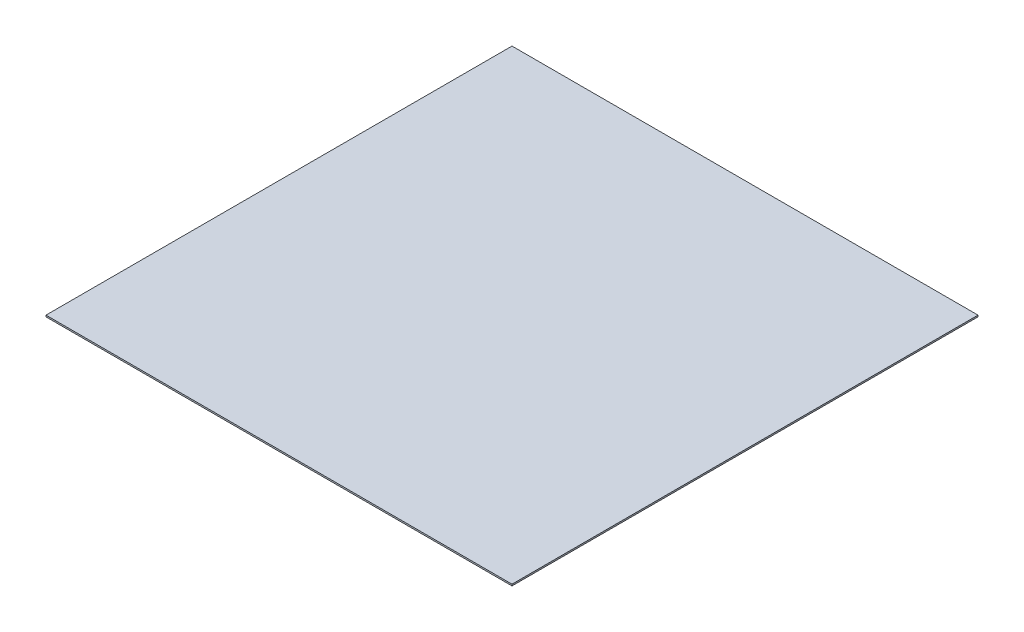
SolidWorks part; units mm, degrees
ref_plane "Front Plane" through (0, 0, 0) normal (0, 0, 1) x (1, 0, 0)
ref_plane "Top Plane" through (0, 0, 0) normal (0, 1, 0) x (1, 0, 0)
ref_plane "Right Plane" through (0, 0, 0) normal (1, 0, 0) x (0, 0, -1)
sketch "Sketch1" plane through (0, 0, 0) normal (0, 1, 0) x (1, 0, 0)
  line L1 (-750, 750) -> (750, 750)
  line L2 (-750, 750) -> (-750, -750)
  line L3 (-750, -750) -> (750, -750)
  line L4 (750, 750) -> (750, -750)
  line L5 (-750, 750) -> (750, -750) construction
  line L6 (-750, -750) -> (750, 750) construction
  point P0 (0, 0)
  dimension "D1" = 1500
  dimension "D2" = 1500
extrude "Boss-Extrude1" add sketch "Sketch1" against normal blind 5
